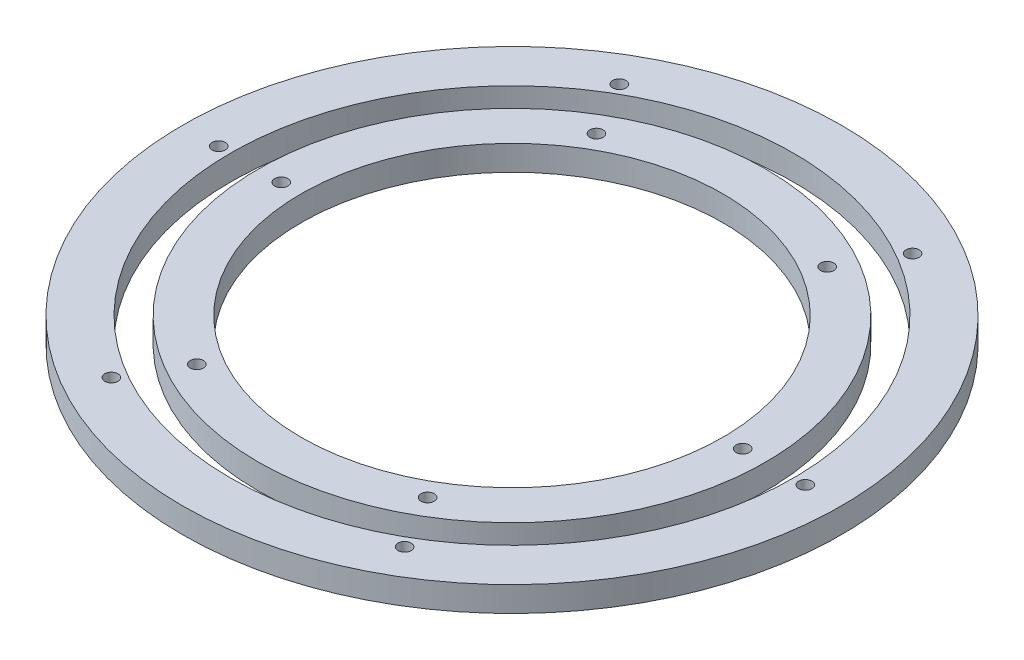
SolidWorks part; units mm, degrees
material "Pine"
ref_plane "Front Plane" through (0, 0, 0) normal (0, 0, 1) x (1, 0, 0)
ref_plane "Top Plane" through (0, 0, 0) normal (0, 1, 0) x (1, 0, 0)
ref_plane "Right Plane" through (0, 0, 0) normal (1, 0, 0) x (0, 0, -1)
sketch "Sketch1" plane through (0, 0, 0) normal (0, 1, 0) x (1, 0, 0)
  circle A0 centre (0, 0) radius 250
  circle A1 centre (0, 0) radius 160
  dimension "D1" = 500
  dimension "D2" = 320
extrude "Boss-Extrude1" add sketch "Sketch1" along normal mid plane 19
sketch "Sketch2" plane through (0, 9.5, 0) normal (0, 1, 0) x (1, 0, 0)
  line L0 (0, -1000) -> (0, 49000) construction
  line L1 (-1000, 0) -> (49000, 0) construction
  line L2 (-500, 866.0254) -> (24500, -42435.2448) construction
  line L3 (-500, -866.0254) -> (24500, 42435.2448) construction
  circle A0 centre (0, 0) radius 192.5
  circle A1 centre (0, 0) radius 213.5
  circle A2 centre (111.25, 192.6907) radius 5
  circle A3 centre (222.5, 0) radius 5
  circle A4 centre (-222.5, 0) radius 5
  circle A5 centre (-111.25, 192.6907) radius 5
  circle A6 centre (111.25, -192.6907) radius 5
  circle A7 centre (-111.25, -192.6907) radius 5
  dimension "D1" = 427
  dimension "D2" = 385
  dimension "D3" = 10
  dimension "D4" = 10
  dimension "D5" = 222.5
  dimension "D6" = 222.5
  dimension "D7" = 21
  dimension "D8" = 60
  dimension "D9" = 60
extrude "Cut-Extrude1" cut sketch "Sketch2" against normal through all
sketch "Sketch3" plane through (0, 9.5, 0) normal (0, 1, 0) x (1, 0, 0)
  line L0 (-1000, 0) -> (49000, 0) construction
  line L1 (0, -1000) -> (0, 49000) construction
  line L2 (-500, -866.0254) -> (24500, 42435.2448) construction
  line L3 (-500, 866.0254) -> (24500, -42435.2448) construction
  circle A0 centre (-87.5, 151.5544) radius 5
  circle A1 centre (-175, 0) radius 5
  circle A2 centre (175, 0) radius 5
  circle A3 centre (87.5, 151.5544) radius 5
  circle A4 centre (87.5, -151.5544) radius 5
  circle A5 centre (-87.5, -151.5544) radius 5
  point P12 (0, 0)
  point P14 (0, 0)
  dimension "D1" = 10
  dimension "D2" = 10
  dimension "D3" = 175
  dimension "D4" = 175
extrude "Cut-Extrude2" cut sketch "Sketch3" against normal through all
